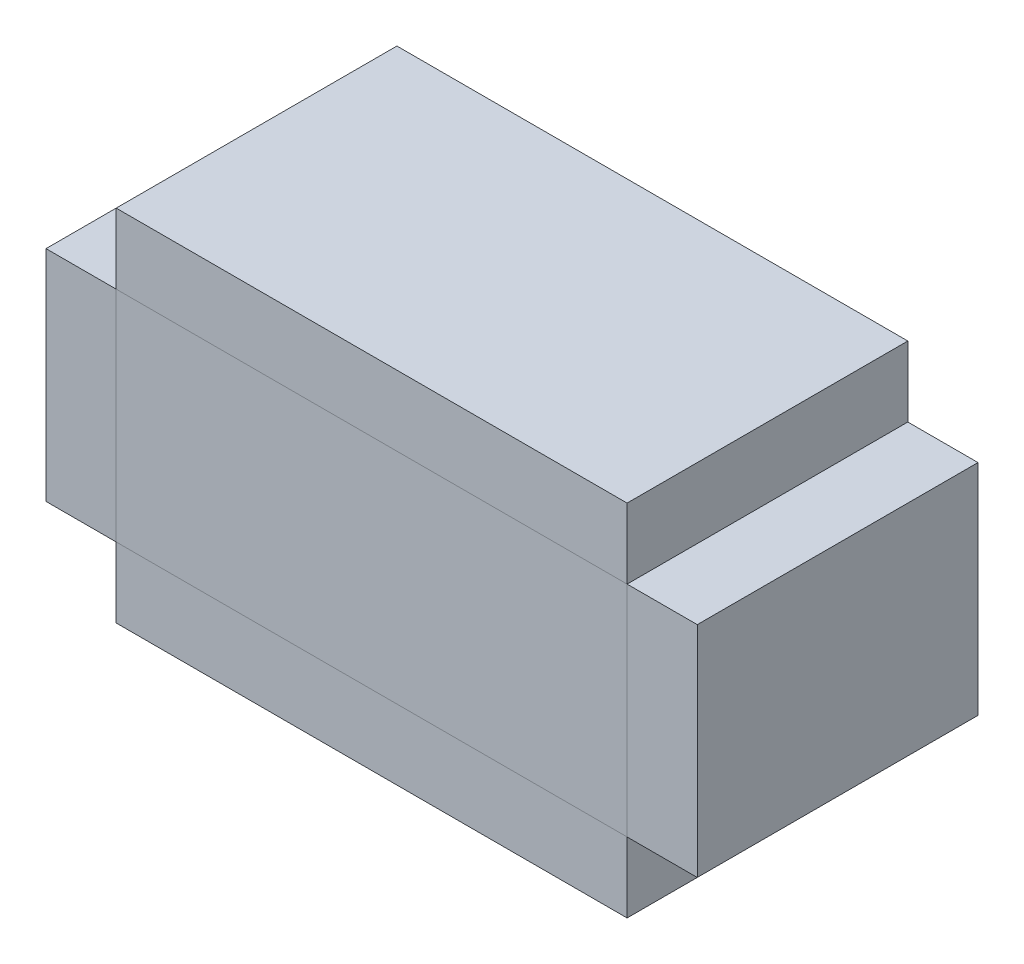
SolidWorks part; units mm, degrees
ref_plane "Front" through (0, 0, 0) normal (0, 0, 1) x (1, 0, 0)
ref_plane "Top" through (0, 0, 0) normal (0, 1, 0) x (1, 0, 0)
ref_plane "Right" through (0, 0, 0) normal (1, 0, 0) x (0, 0, -1)
sketch "Sketch1" plane through (0, 0, 0) normal (0, 0, 1) x (1, 0, 0)
  line L0 (-8.4059, 1.562) -> (65.2541, 1.562) construction
  line L1 (-28.8925, -15.24) -> (28.8925, -15.24)
  line L2 (-28.8925, -15.24) -> (-28.8925, 9.525)
  line L3 (-28.8925, 9.525) -> (28.8925, 9.525)
  line L4 (28.8925, -15.24) -> (28.8925, 9.525)
  line L5 (-5.5562, 0) -> (5.5563, 0) construction
  line L6 (-7.8423, 4.3815) -> (-5.5563, 4.3815) construction
  line L7 (-7.8423, 4.3815) -> (-7.8423, -4.3815) construction
  line L8 (-7.8423, -4.3815) -> (-5.5563, -4.3815) construction
  line L9 (-5.5563, 4.3815) -> (-5.5563, -4.3815) construction
  line L10 (5.5563, 3.7465) -> (7.8423, 3.7465) construction
  line L11 (5.5563, 3.7465) -> (5.5563, -3.4925) construction
  line L12 (5.5563, -3.4925) -> (7.8423, -3.4925) construction
  line L13 (7.8423, 3.7465) -> (7.8423, -3.4925) construction
  line L14 (-2.54, -14.351) -> (2.54, -14.351) construction
  line L15 (-2.54, -14.351) -> (-2.54, -11.811) construction
  line L16 (-2.54, -11.811) -> (2.54, -11.811) construction
  line L17 (2.54, -14.351) -> (2.54, -11.811) construction
  line L18 (0, 9.525) -> (0, 0) construction
  line L19 (0, 0) -> (0, -11.811) construction
  circle A0 centre (-28.8925, 9.525) radius 7.9375 construction
  circle A1 centre (28.8925, -15.24) radius 7.9375 construction
  arc A2 (-2.54, -11.811) -> (2.54, -11.811) centre (0, -11.811) cw construction
  point P7 (-36.83, 9.525)
  point P8 (-28.8925, 17.4625)
  point P9 (28.8925, -23.1775)
  point P10 (36.83, -15.24)
  dimension "D4" = 15.875
  dimension "D10" = 2.54
  dimension "D1" = 73.66
  dimension "D2" = 40.64
  dimension "D3" = 73.66
  dimension "D5" = 2.286
  dimension "D6" = 2.286
  dimension "D7" = 7.239
  dimension "D8" = 8.763
  dimension "D9" = 9.525
  dimension "D11" = 2.54
  dimension "D12" = 21.336
  dimension "D13" = 11.1125
  dimension "D14" = 0.635
extrude "Boss-Extrude1" add sketch "Sketch1" against normal mid plane 31.75
sketch "Sketch2" plane through (0, 0, -15.875) normal (0, 0, -1) x (-1, 0, 0)
  line L0 (28.8925, -15.24) -> (-28.8925, -15.24) construction
  line L1 (28.8925, 9.525) -> (36.83, 9.525)
  line L2 (28.8925, 9.525) -> (28.8925, -15.24)
  line L3 (28.8925, -15.24) -> (36.83, -15.24)
  line L4 (36.83, 9.525) -> (36.83, -15.24)
  line L5 (28.8925, -15.24) -> (-28.8925, -15.24)
  line L6 (28.8925, -15.24) -> (28.8925, -23.1775)
  line L7 (28.8925, -23.1775) -> (-28.8925, -23.1775)
  line L8 (-28.8925, -15.24) -> (-28.8925, -23.1775)
  line L10 (-28.8925, -15.24) -> (-36.83, -15.24)
  line L11 (-28.8925, -15.24) -> (-28.8925, 9.525)
  line L12 (-28.8925, 9.525) -> (-36.83, 9.525)
  line L13 (-36.83, -15.24) -> (-36.83, 9.525)
  line L14 (-28.8925, 9.525) -> (28.8925, 9.525)
  line L15 (-28.8925, 9.525) -> (-28.8925, 17.4625)
  line L16 (-28.8925, 17.4625) -> (28.8925, 17.4625)
  line L17 (28.8925, 9.525) -> (28.8925, 17.4625)
extrude "Boss-Extrude2" add sketch "Sketch2" against normal up to surface (31.75 mm away) separate body
